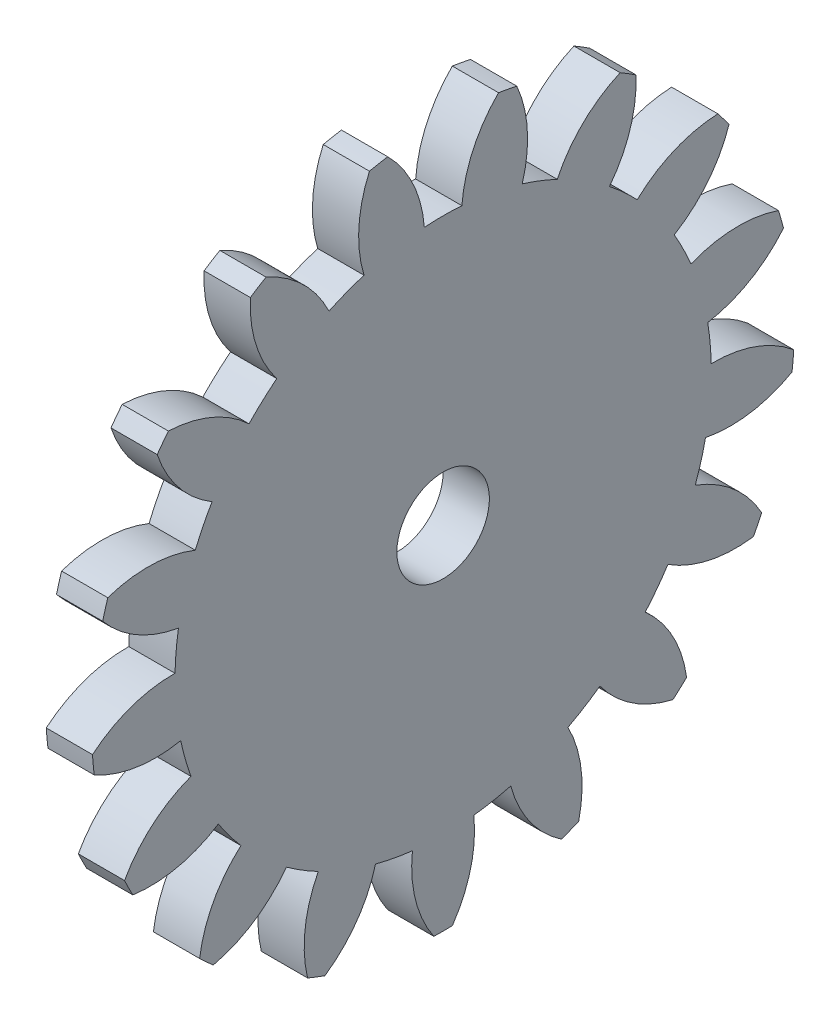
SolidWorks part; units mm, degrees
ref_plane "Plane1" through (0, 0, 0) normal (0, 0, 1) x (1, 0, 0)
ref_plane "Plane2" through (0, 0, 0) normal (0, 1, 0) x (1, 0, 0)
ref_plane "Plane3" through (0, 0, 0) normal (1, 0, 0) x (0, 0, -1)
sketch "HoldingSke" plane through (0, 0, 0) normal (0, 1, 0) x (1, 0, 0)
  line L0 (0, 0) -> (0.2391, -0.0731)
  line L1 (-15, 0) -> (100, 0) construction
  line L2 (0, 0) -> (-2.1039, 2.3779)
  line L3 (0, 0) -> (-11.863, 4.5341)
  line L4 (0, 0) -> (8.2586, 2.5249)
  line L5 (0, 0) -> (-46.8476, -17.4728)
  line L6 (0, 0) -> (-4.1448, -2.7965)
  line L7 (-2.1039, 2.3779) -> (8.6586, 51.2059)
  line L8 (-76.2, 54.61) -> (-74.4, 54.61)
  line L9 (-71.009, 38.7566) -> (-53.1078, 45.2721)
  line L10 (-76.2, 71.12) -> (104.1128, 71.12)
  line L11 (0, 0) -> (-5, 0)
  line L12 (-76.2, 101.6) -> (-76.073, 101.6)
  line L13 (24.9733, 27.94) -> (52.9518, 28.4284)
  line L14 (24.9733, 27.94) -> (24.9743, 27.94)
  line L15 (24.9733, 27.94) -> (100.4006, 29.5858)
  line L16 (-63.627, -4) -> (-12.827, -4)
  circle A0 centre (0, 0) radius 5
  circle A1 centre (0, 0) radius 28.999
  circle A2 centre (0, 0) radius 37.5
  circle A3 centre (0, 0) radius 5
  dimension "MHD" = 57.998
  dimension "Hub_dia" = 75
  dimension "Bore" = 10
  dimension "MBD" = 10
  dimension "Num_teeth" = 17
  dimension "Pitch" = 0.25
  dimension "Overall_len" = 50
  dimension "Show_teeth" = 17
  dimension "Thickness" = 5
  dimension "OAL" = 50.0001
  dimension "T_dim" = 1.8
  dimension "Ap" = 20
  dimension "H" = 19.05
  dimension "Pitch_radius" = 180.3128
  dimension "Width" = 5
  dimension "Backlash" = 0.127
  dimension "Addendum_fac" = 1
  dimension "Dedendum_fac" = 1.25
  dimension "Clearance_fac" = 0.25
  dimension "Dedendum_add" = 0.001
  dimension "Module" = 4
sketch "BasProSke" plane through (0, 0, 0) normal (0, 1, 0) x (1, 0, 0)
  line L0 (-10, 0) -> (60, 0) construction
  line L1 (0, 0) -> (0, 38)
  line L2 (0, 0) -> (5, 0)
  line L3 (5, 0) -> (5, 38)
  line L4 (5, 38) -> (0, 38)
  dimension "Thickness" = 5
  dimension "Diameter" = 76
revolve "Base-Revolve" add sketch "BasProSke" angle 360 about L0
sketch "TooCutSke" plane through (0, 0, 0) normal (1, 0, 0) x (0, 0, -1)
  line L1 (0, 0) -> (0, 107) construction
  line L2 (0, 0) -> (-3.3592, 33.8336) construction
  line L3 (0, 0) -> (-12.449, 66.5961) construction
  line L4 (-3.3592, 33.8336) -> (-6.2245, 33.298) construction
  arc A0 (2.0303, 28.9278) -> (-2.0303, 28.9278) centre (0, 0) ccw
  arc A1 (6.0163, 37.5464) -> (-6.0163, 37.5464) centre (0, 0) ccw
  circle A2 centre (0, 0) radius 34 construction
  circle A3 centre (0, 0) radius 31.9495 construction
  arc A4 (-2.0303, 28.9278) -> (-6.0163, 37.5464) centre (-15.5905, 27.8875) ccw
  arc A5 (6.0163, 37.5464) -> (2.0303, 28.9278) centre (15.5905, 27.8875) ccw
  dimension "Root_dia" = 57.998
  dimension "Overcut_dia" = 76.0508
  dimension "Pitch_dia" = 68
  dimension "Base_dia" = 63.8991
  dimension "Flank_rad" = 13.6
  dimension "Half_ang" = 10.588
  dimension "Half_CT" = 2.9149
extrude "ToothCut" cut sketch "TooCutSke" along normal through all
fillet "Breaks" [suppressed] radius 0.08
fillet "RootFillets" [suppressed] radius 1.001
pattern_circular "TeethCuts" count 17 every 21.176 about axis through (-10, 0, 0) along (1, 0, 0) of "ToothCut", "RootFillets", "Breaks"
sketch "HubNeaOneSke" plane through (0, 0, 0) normal (-1, 0, 0) x (0, 0, 1)
  circle A0 centre (0, 0) radius 28.999
  dimension "Diameter" = 57.998
extrude "HubNearOne" [suppressed] add sketch "HubNeaOneSke" along normal blind 45.0001
sketch "HubNeaBotSke" plane through (0, 0, 0) normal (-1, 0, 0) x (0, 0, 1)
  circle A0 centre (0, 0) radius 28.999
  dimension "Diameter" = 57.998
extrude "HubNearBoth" [suppressed] add sketch "HubNeaBotSke" along normal blind 22.5
ref_plane "FarPln" through (5, 0, 0) normal (1, 0, 0) x (0, 0, -1)
sketch "HubFarSke" plane through (5, 0, 0) normal (1, 0, 0) x (0, 0, -1)
  circle A0 centre (0, 0) radius 28.999
  dimension "Diameter" = 57.998
extrude "HubFar" [suppressed] add sketch "HubFarSke" along normal blind 22.5
sketch "BorSke" plane through (0, 0, 0) normal (1, 0, 0) x (0, 0, -1)
  circle A0 centre (0, 0) radius 5
  dimension "Diameter" = 10
extrude "Bore" cut sketch "BorSke" along normal mid plane 100.0001
sketch "KeySke" plane through (0, 0, 0) normal (1, 0, 0) x (0, 0, -1)
  line L0 (-2, 0) -> (-2, 6.8)
  line L1 (-2, 6.8) -> (2, 6.8)
  line L2 (2, 6.8) -> (2, 0)
  line L3 (0, 0) -> (0, 34) construction
  line L4 (-2, 0) -> (2, 0)
  dimension "Offset" = 6.8
  dimension "Width" = 4
extrude "Keyway" [suppressed] cut sketch "KeySke" along normal mid plane 100.0001
pattern_circular "Keyway2" [suppressed] count 2 every 90 about axis through (-10, 0, 0) along (1, 0, 0)
equation "' \"Module@HoldingSke\" = 6.35"
equation "' \"Num_teeth@HoldingSke\" = 12"
equation "' \"Ap@HoldingSke\" =  20"
equation "' \"Ap@HoldingSke\" = 20"
equation "' \"Width@HoldingSke\" = 0.5 * 25.4"
equation "' \"Hub_dia@HoldingSke\"= 1 * 25.4"
equation "' \"Hub_dia@HoldingSke\" = 1 * 25.4"
equation "' \"Overall_len@HoldingSke\" = 1.0 * 25.4"
equation "' \"Bore@HoldingSke\" = 0.75 * 25.4"
equation "' \"T_dim@HoldingSke\" = 0.1 * 25.4"
equation "' \"Width@KeySke\" = 0.25 * 25.4"
equation "' \"Show_teeth@HoldingSke\" = 13"
equation "' \"Backlash@HoldingSke\" = 0.009 * 25.4"
equation "' \"Addendum_fac@HoldingSke\" = 1.0"
equation "' \"Dedendum_fac@HoldingSke\" = 1.25"
equation "' \"Dedendum_add@HoldingSke\" = 0.00005 * 25.4"
equation "' \"Clearance_fac@HoldingSke\" = 0.25"
equation "\"Pitch@HoldingSke\" = 1 / \"Module@HoldingSke\""
equation "\"Overcut_dia@TooCutSke\" = (\"Num_teeth@HoldingSke\" + 2 * \"Addendum_fac@HoldingSke\") / \"Pitch@HoldingSke\" + 0.002 * 25.4"
equation "\"Pitch_dia@TooCutSke\" = \"Num_teeth@HoldingSke\" / \"Pitch@HoldingSke\""
equation "\"Base_dia@TooCutSke\" = \"Num_teeth@HoldingSke\" / \"Pitch@HoldingSke\" * cos((\"Ap@HoldingSke\"  * 3.14159265 / 180))"
equation "\"Root_dia@TooCutSke\" = (\"Num_teeth@HoldingSke\" + 2) / \"Pitch@HoldingSke\" - 2 * (\"Addendum_fac@HoldingSke\" + \"Dedendum_fac@HoldingSke\") / \"Pitch@HoldingSke\" - \"Dedendum_add@HoldingSke\" * 2"
equation "\"Half_ang@TooCutSke\" = 180 / \"Num_teeth@HoldingSke\""
equation "\"Half_CT@TooCutSke\" = \"Num_teeth@HoldingSke\" / \"Pitch@HoldingSke\" * sin((3.14159265 / 2 / \"Num_teeth@HoldingSke\")) / 2 - 7 * \"Backlash@HoldingSke\" / 4"
equation "\"Flank_rad@TooCutSke\" = \"Num_teeth@HoldingSke\" / \"Pitch@HoldingSke\" / 5"
equation "\"Radius@RootFillets\" = \"Clearance_fac@HoldingSke\" / \"Pitch@HoldingSke\" + \"Dedendum_add@HoldingSke\""
equation "\"Break_rad@Breaks\" = 0.02 / \"Pitch@HoldingSke\""
equation "\"Thickness@HoldingSke\" = \"Width@HoldingSke\""
equation "\"OAL@HoldingSke\" = \"Thickness@HoldingSke\""
equation "\"MHD@HoldingSke\" = (\"Num_teeth@HoldingSke\" + 2) / \"Pitch@HoldingSke\" - 2 * (\"Addendum_fac@HoldingSke\" + \"Dedendum_fac@HoldingSke\")  / \"Pitch@HoldingSke\" - \"Dedendum_add@HoldingSke\" * 2"
equation "\"MBD@HoldingSke\" = (\"Num_teeth@HoldingSke\" + 2) / \"Pitch@HoldingSke\" - 2 * (\"Addendum_fac@HoldingSke\" + \"Dedendum_fac@HoldingSke\")  / \"Pitch@HoldingSke\" - \"Dedendum_add@HoldingSke\" * 2 - 0.002 * 25.4"
equation "\"MHD@HoldingSke\" = ((sgn( \"MHD@HoldingSke\" - \"Hub_dia@HoldingSke\" )-1)*( \"MHD@HoldingSke\" - \"Hub_dia@HoldingSke\" ))/-2+ \"Hub_dia@HoldingSke\""
equation "\"MBD@HoldingSke\" = ((sgn( \"MBD@HoldingSke\" - \"Bore@HoldingSke\" )-1)*( \"MBD@HoldingSke\" - \"Bore@HoldingSke\" ))/-2+ \"Bore@HoldingSke\""
equation "\"OAL@HoldingSke\" = ((sgn( \"OAL@HoldingSke\" - \"Overall_len@HoldingSke\" )+1)*( \"OAL@HoldingSke\" - \"Overall_len@HoldingSke\" ))/2 + \"Overall_len@HoldingSke\" + 0.000002 * 25.4"
equation "\"Num_teeth@TeethCuts\" = int( \"Show_teeth@HoldingSke\" ) + 1"
equation "\"Num_teeth@TeethCuts\" = ((sgn( \"Num_teeth@TeethCuts\" - \"Num_teeth@HoldingSke\" )-1)*( \"Num_teeth@TeethCuts\" - \"Num_teeth@HoldingSke\" ))/-2+ \"Num_teeth@HoldingSke\""
equation "\"Num_teeth@TeethCuts\" = ((sgn( \"Num_teeth@TeethCuts\" - 2.0)+1)*( \"Num_teeth@TeethCuts\" - 2.0))/2 +2.0"
equation "\"Angle@TeethCuts\" = 360.0 / \"Num_teeth@HoldingSke\""
equation "\"Diameter@BasProSke\" = (\"Num_teeth@HoldingSke\" + 2 * \"Addendum_fac@HoldingSke\") / \"Pitch@HoldingSke\""
equation "\"Thickness@BasProSke\"  = \"Thickness@HoldingSke\""
equation "' \"Fillet_rad@BasProSke\" =  \"Thickness@HoldingSke\" * 0.05"
equation "' \"Fillet_rad@BasProSke\" = \"Thickness@HoldingSke\" * 0.05"
equation "\"MHD@HoldingSke\" = ((sgn( \"MHD@HoldingSke\" - \"Root_dia@TooCutSke\" )-1)*( \"MHD@HoldingSke\" - \"Root_dia@TooCutSke\" ))/-2+ \"Root_dia@TooCutSke\""
equation "\"Diameter@HubNeaOneSke\" = \"MHD@HoldingSke\""
equation "\"Length@HubNearOne\" = \"OAL@HoldingSke\" - \"Thickness@BasProSke\""
equation "\"Diameter@HubNeaBotSke\" = \"MHD@HoldingSke\""
equation "\"Length@HubNearBoth\" = ( \"OAL@HoldingSke\" - \"Thickness@BasProSke\" ) / 2.0"
equation "\"Thickness@FarPln\" = \"Thickness@BasProSke\""
equation "\"Diameter@HubFarSke\" = \"MHD@HoldingSke\""
equation "\"Length@HubFar\" = ( \"OAL@HoldingSke\" - \"Thickness@BasProSke\" ) / 2.0"
equation "\"Diameter@BorSke\" = \"MBD@HoldingSke\""
equation "\"D1@Bore\" = \"OAL@HoldingSke\" * 2.0"
equation "\"D1@Keyway\" = \"OAL@HoldingSke\" * 2.0"
equation "\"Offset@KeySke\" = \"T_dim@HoldingSke\" + \"MBD@HoldingSke\" / 2.0"
